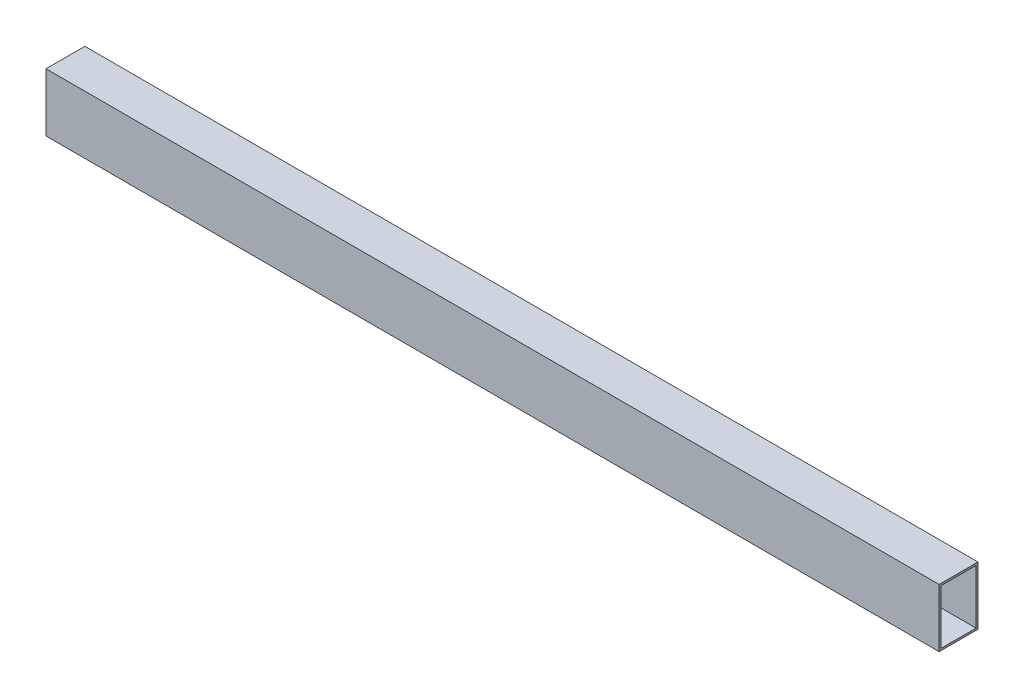
SolidWorks part; units mm, degrees
ref_plane "Front" through (0, 0, 0) normal (0, 0, 1) x (1, 0, 0)
ref_plane "Top" through (0, 0, 0) normal (0, 1, 0) x (1, 0, 0)
ref_plane "Right" through (0, 0, 0) normal (1, 0, 0) x (0, 0, -1)
sketch "草图1" plane through (0, 0, 0) normal (0, 1, 0) x (1, 0, 0)
  line L0 (0, 0) -> (460, 0)
  dimension "D1" = 460
other "铝管 20X30X1(1)"
ref_plane "基准面1" through (0, 0, 0) normal (1, 0, 0) x (0, 0, -1)
sketch "草图11" plane through (0, 0, 0) normal (1, 0, 0) x (0, 0, -1)
  line L1 (-10, -15) -> (10, -15)
  line L2 (-10, -15) -> (-10, 15)
  line L3 (-10, 15) -> (10, 15)
  line L4 (10, -15) -> (10, 15)
  line L5 (-10, -15) -> (10, 15) construction
  line L6 (-10, 15) -> (10, -15) construction
  line L7 (-9, -14) -> (9, -14)
  line L8 (-9, -14) -> (-9, 14)
  line L9 (-9, 14) -> (9, 14)
  line L10 (9, -14) -> (9, 14)
  line L11 (-9, -14) -> (9, 14) construction
  line L12 (-9, 14) -> (9, -14) construction
  point P0 (0, 0)
  point P6 (0, 0)
  point P11 (0, 0)
  dimension "D1" = 20
  dimension "D2" = 30
  dimension "D3" = 28
  dimension "D4" = 18
